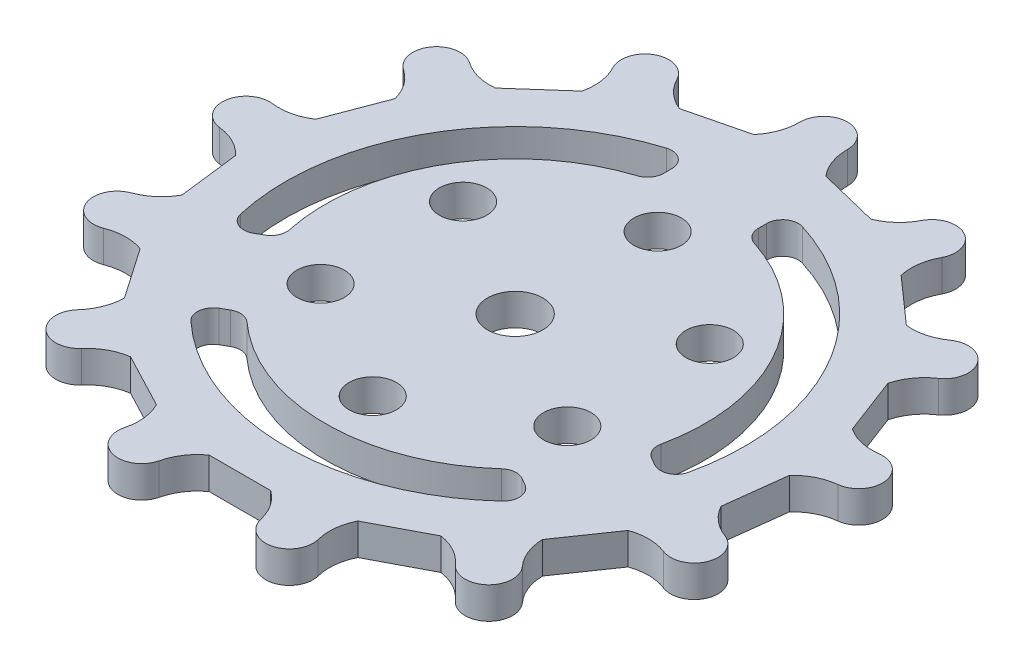
SolidWorks part; units mm, degrees
material "1060 Alloy"
ref_plane "Front Plane" through (0, 0, 0) normal (0, 0, 1) x (1, 0, 0)
ref_plane "Top Plane" through (0, 0, 0) normal (0, 1, 0) x (1, 0, 0)
ref_plane "Right Plane" through (0, 0, 0) normal (1, 0, 0) x (0, 0, -1)
sketch "Sketch1" plane through (0, 0, 0) normal (0, 1, 0) x (1, 0, 0)
  line L0 (0, 0) -> (9.2241, 0) construction
  line L1 (0, 0) -> (8.3653, 4.8297) construction
  line L2 (0, 22.5) -> (0, 19.5) construction
  line L3 (2.2759, 17.3514) -> (6.0484, 16.4216)
  line L4 (10.0788, 14.3062) -> (12.987, 11.7298)
  line L5 (15.5728, 7.9837) -> (16.9505, 4.3508)
  line L6 (17.4992, -0.1679) -> (17.0309, -4.0249)
  line L7 (15.4168, -8.2809) -> (13.2096, -11.4785)
  line L8 (9.8025, -14.4969) -> (6.3622, -16.3025)
  line L9 (1.9427, -17.3918) -> (-1.9427, -17.3918)
  line L10 (-6.3622, -16.3025) -> (-9.8025, -14.4969)
  line L11 (-13.2096, -11.4785) -> (-15.4168, -8.2809)
  line L12 (-17.0309, -4.0249) -> (-17.4992, -0.1679)
  line L13 (-16.9505, 4.3508) -> (-15.5728, 7.9837)
  line L14 (-12.987, 11.7298) -> (-10.0788, 14.3062)
  line L15 (-6.0484, 16.4216) -> (-2.2759, 17.3514)
  circle A0 centre (0, 0) radius 1.75
  circle A2 centre (0, 9) radius 1.5
  circle A3 centre (7.7942, -4.5) radius 1.5
  circle A4 centre (-7.7942, -4.5) radius 1.5
  circle A5 centre (7.7942, 4.5) radius 1.5
  circle A6 centre (0, -9) radius 1.5
  circle A7 centre (-7.7942, 4.5) radius 1.5
  arc A8 (1.4998, 19.4736) -> (-1.4998, 19.4736) centre (0, 19.5) ccw
  arc A9 (-1.5, 19.5) -> (-2.2759, 17.3514) centre (-4.7471, 19.4582) cw
  arc A10 (1.5, 19.5) -> (2.2759, 17.3514) centre (4.7471, 19.4582) ccw
  arc A11 (7.7339, 17.9635) -> (6.0484, 16.4216) centre (4.8393, 19.4355) cw
  arc A12 (10.3778, 16.546) -> (7.7218, 17.94) centre (9.0621, 17.2664) ccw
  arc A13 (10.3903, 16.5693) -> (10.0788, 14.3062) centre (13.246, 15.0233) ccw
  arc A14 (15.1961, 12.3117) -> (12.987, 11.7298) centre (13.3171, 14.9603) cw
  arc A15 (16.8784, 9.828) -> (15.1745, 12.2965) centre (16.0482, 11.0773) ccw
  arc A16 (16.9003, 9.8428) -> (15.5728, 7.9837) centre (18.7104, 7.1467) ccw
  arc A17 (19.177, 3.8395) -> (16.9505, 4.3508) centre (18.7441, 7.0579) cw
  arc A18 (19.5124, 0.8584) -> (19.1508, 3.8361) centre (19.3578, 2.3505) ccw
  arc A19 (19.5386, 0.8614) -> (17.4992, -0.1679) centre (19.8885, -2.3671) ccw
  arc A20 (18.7647, -5.5123) -> (17.0309, -4.0249) centre (19.8771, -2.4614) cw
  arc A21 (17.6763, -8.3077) -> (18.7399, -5.5031) centre (18.2328, -6.9148) ccw
  arc A22 (17.7009, -8.3173) -> (15.4168, -8.2809) centre (16.5104, -11.3386) ccw
  arc A23 (14.0537, -13.6013) -> (13.2096, -11.4785) centre (16.4564, -11.4168) cw
  arc A24 (11.7908, -15.5707) -> (14.036, -13.5817) centre (12.9309, -14.596) ccw
  arc A25 (11.8081, -15.5906) -> (9.8025, -14.4969) centre (9.3499, -17.7126) ccw
  arc A26 (6.1231, -18.5744) -> (6.3622, -16.3025) centre (9.2658, -17.7567) cw
  arc A27 (3.2041, -19.2666) -> (6.1165, -18.5488) centre (4.6667, -18.9334) ccw
  arc A28 (3.2102, -19.2923) -> (1.9427, -17.3918) centre (0.0475, -20.0288) ccw
  arc A29 (-3.2102, -19.2923) -> (-1.9427, -17.3918) centre (-0.0475, -20.0288) cw
  arc A30 (-6.1165, -18.5488) -> (-3.2041, -19.2666) centre (-4.6667, -18.9334) ccw
  arc A31 (-6.1231, -18.5744) -> (-6.3622, -16.3025) centre (-9.2658, -17.7567) ccw
  arc A32 (-11.8081, -15.5906) -> (-9.8025, -14.4969) centre (-9.3499, -17.7126) cw
  arc A33 (-14.036, -13.5817) -> (-11.7908, -15.5707) centre (-12.9309, -14.596) ccw
  arc A34 (-14.0537, -13.6013) -> (-13.2096, -11.4785) centre (-16.4564, -11.4168) ccw
  arc A35 (-17.7009, -8.3173) -> (-15.4168, -8.2809) centre (-16.5104, -11.3386) cw
  arc A36 (-18.7399, -5.5031) -> (-17.6763, -8.3077) centre (-18.2328, -6.9148) ccw
  arc A37 (-18.7647, -5.5123) -> (-17.0309, -4.0249) centre (-19.8771, -2.4614) ccw
  arc A38 (-19.5386, 0.8614) -> (-17.4992, -0.1679) centre (-19.8885, -2.3671) cw
  arc A39 (-19.1508, 3.8361) -> (-19.5124, 0.8584) centre (-19.3578, 2.3505) ccw
  arc A40 (-19.177, 3.8395) -> (-16.9505, 4.3508) centre (-18.7441, 7.0579) ccw
  arc A41 (-16.9003, 9.8428) -> (-15.5728, 7.9837) centre (-18.7104, 7.1467) cw
  arc A42 (-15.1745, 12.2965) -> (-16.8784, 9.828) centre (-16.0482, 11.0773) ccw
  arc A43 (-15.1961, 12.3117) -> (-12.987, 11.7298) centre (-13.3171, 14.9603) ccw
  arc A44 (-10.3903, 16.5693) -> (-10.0788, 14.3062) centre (-13.246, 15.0233) cw
  arc A45 (-7.7218, 17.94) -> (-10.3778, 16.546) centre (-9.0621, 17.2664) ccw
  arc A46 (-7.7339, 17.9635) -> (-6.0484, 16.4216) centre (-4.8393, 19.4355) ccw
  point P13 (0, 0)
  point P22 (0, 0)
  point P28 (0, 21)
  point P140 (0, 0)
  point P165 (0, 0)
  dimension "D1" = 3.5
  dimension "D2" = 13
  dimension "D3" = 3
  dimension "D4" = 9
  dimension "D7" = 3
  dimension "D8" = 9
  dimension "D10" = 3
  dimension "D11" = 19.5
  dimension "D12" = 13
  dimension "D6" = 30
  dimension "D5" = 3
  dimension "D9" = 3
extrude "Boss-Extrude3" add sketch "Sketch1" along normal blind 2 contours A46 A45 A44 L14 A43 A42 A41 L13 A40 A39 A38 L12 A37 A36 A35 L11 A34 A33 A32 L10 A31 A30 A29 L9 A28 A27 A26 L8 A25 A24 A23 L7 A22 A21 A20
sketch "Sketch3" plane through (0, 2, 0) normal (0, 1, 0) x (1, 0, 0)
  line L0 (-3, 14.1863) -> (-3, 11.619)
  line L1 (3, 14.1863) -> (3, 11.619)
  line L2 (13.7857, -4.4951) -> (11.5623, -3.2114)
  line L3 (10.7857, -9.6912) -> (8.5623, -8.4076)
  line L4 (-10.7857, -9.6912) -> (-8.5623, -8.4076)
  line L5 (-13.7857, -4.4951) -> (-11.5623, -3.2114)
  arc A0 (-3, 11.619) -> (-11.5623, -3.2114) centre (0, 0) ccw
  arc A1 (-3, 14.1863) -> (-13.7857, -4.4951) centre (0, 0) ccw
  circle A2 centre (0, 9) radius 1.5 construction
  arc A3 (-8.5623, -8.4076) -> (8.5623, -8.4076) centre (0, 0) ccw
  arc A4 (-10.7857, -9.6912) -> (10.7857, -9.6912) centre (0, 0) ccw
  arc A5 (11.5623, -3.2114) -> (3, 11.619) centre (0, 0) ccw
  arc A6 (13.7857, -4.4951) -> (3, 14.1863) centre (0, 0) ccw
  point P20 (0, 0)
  dimension "D1" = 24
  dimension "D2" = 29
  dimension "D3" = 3
  dimension "D4" = 3
  dimension "D5" = 3
extrude "Cut-Extrude1" cut sketch "Sketch3" against normal blind 2
fillet "Fillet1" radius 1 12 edges at (-13.7857, 1, 4.4951) (-10.7857, 1, 9.6912) (8.5623, 1, 8.4076) (-3, 1, -14.1863) (-8.5623, 1, 8.4076) (10.7857, 1, 9.6912) (-11.5623, 1, 3.2114) (-3, 1, -11.619) (13.7857, 1, 4.4951) (11.5623, 1, 3.2114) (3, 1, -11.619) (3, 1, -14.1863)
